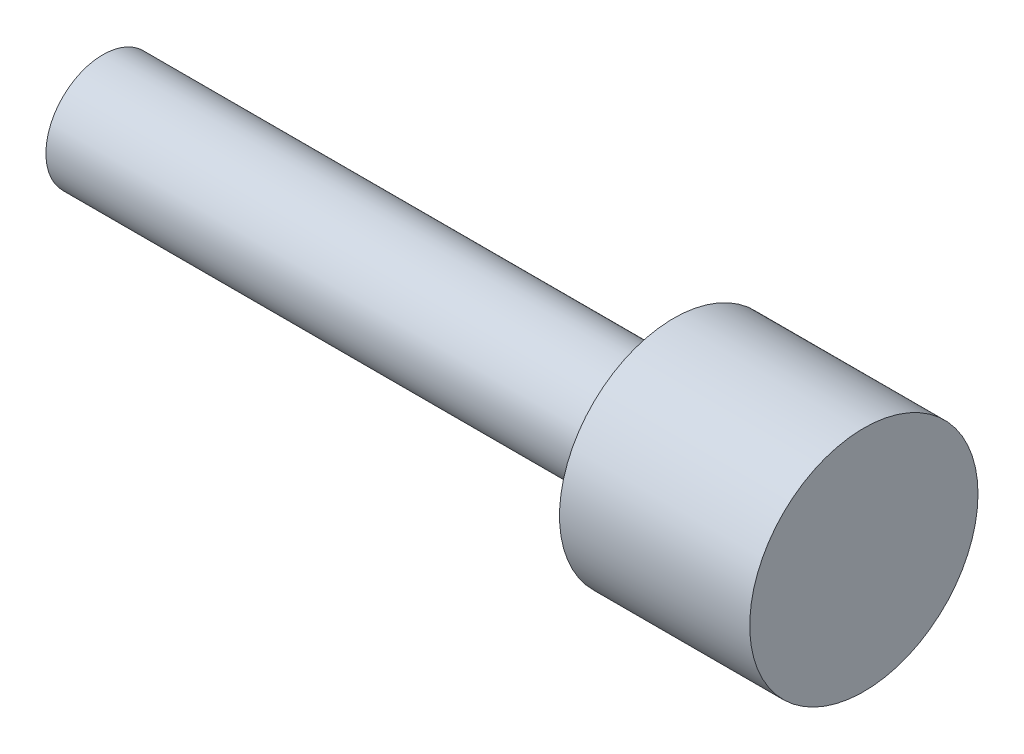
SolidWorks part; units mm, degrees
ref_plane "Front Plane" through (0, 0, 0) normal (0, 0, 1) x (1, 0, 0)
ref_plane "Top Plane" through (0, 0, 0) normal (0, 1, 0) x (1, 0, 0)
ref_plane "Right Plane" through (0, 0, 0) normal (1, 0, 0) x (0, 0, -1)
sketch "Sketch1" plane through (0, 0, 0) normal (0, 0, 1) x (1, 0, 0)
  line L0 (0, 0) -> (0, 3)
  line L1 (0, 3) -> (30, 3)
  line L2 (30, 3) -> (30, 6)
  line L3 (30, 6) -> (40, 6)
  line L4 (40, 6) -> (40, 0)
  line L5 (40, 0) -> (0, 0)
revolve "Revolve1" add sketch "Sketch1" angle 360 about L5
